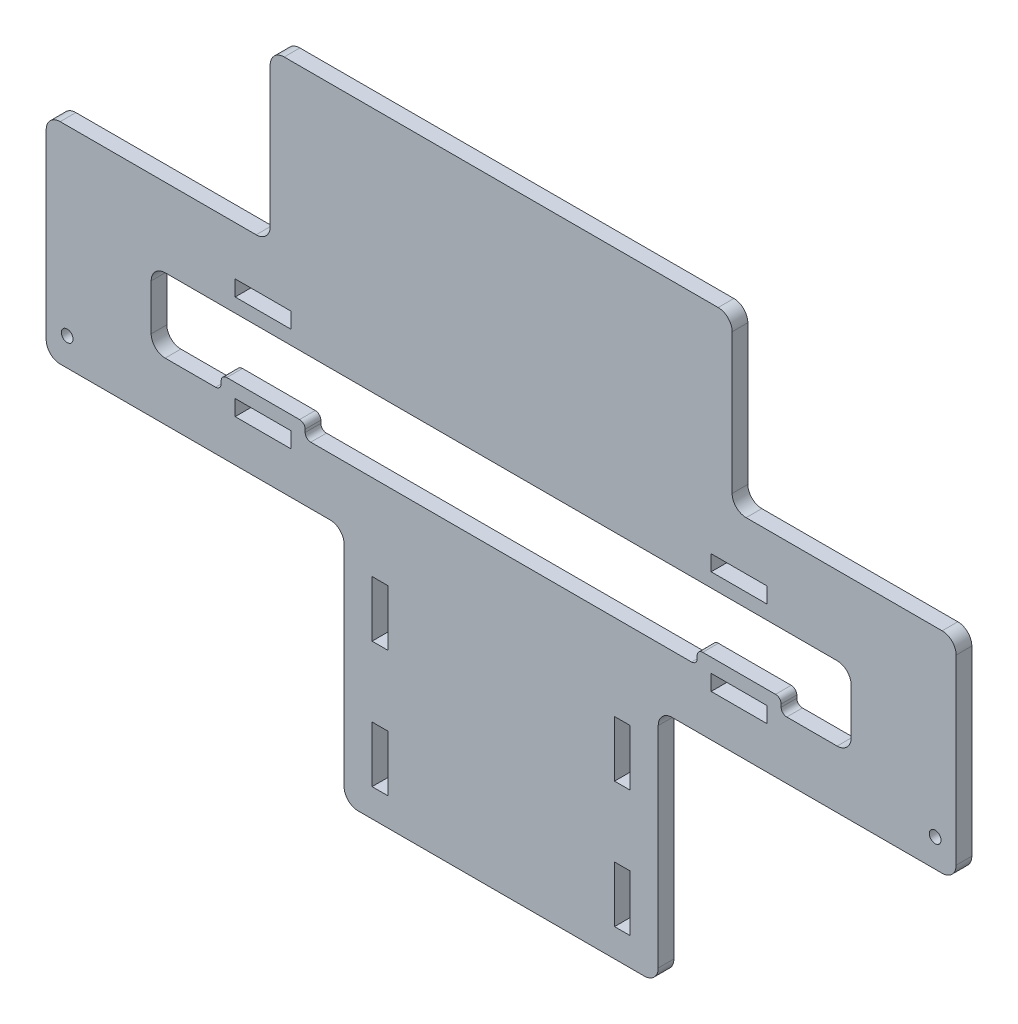
SolidWorks part; units mm, degrees
material "t5ハニカムプラダン"
ref_plane "正面" through (0, 0, 0) normal (0, 0, 1) x (1, 0, 0)
ref_plane "平面" through (0, 0, 0) normal (0, 1, 0) x (1, 0, 0)
ref_plane "右側面" through (0, 0, 0) normal (1, 0, 0) x (0, 0, -1)
sketch "ｽｹｯﾁ1" plane through (0, 0, 0) normal (0, 0, 1) x (1, 0, 0)
  line L0 (0, 0) -> (0, 115) construction
  line L1 (-155, 110) -> (155, 110) construction
  line L2 (-155, 110) -> (-155, -110) construction
  line L3 (-155, -110) -> (155, -110) construction
  line L4 (155, 110) -> (155, -110) construction
  line L5 (-155, 110) -> (155, -110) construction
  line L6 (-155, -110) -> (155, 110) construction
  line L7 (-162.5, 115) -> (162.5, 115)
  line L8 (-162.5, 115) -> (-162.5, -115)
  line L9 (-162.5, -115) -> (162.5, -115)
  line L10 (162.5, 115) -> (162.5, -115)
  line L11 (-162.5, 115) -> (162.5, -115) construction
  line L12 (-162.5, -115) -> (162.5, 115) construction
  line L13 (0, 0) -> (162.5, 0) construction
  circle A0 centre (155, 110) radius 2.1
  circle A1 centre (155, -110) radius 2.1
  circle A2 centre (-155, 110) radius 2.1
  circle A3 centre (-155, -110) radius 2.1
  circle A4 centre (155, -10) radius 2.1
  circle A5 centre (-155, -10) radius 2.1
  point P0 (0, 0)
  point P6 (0, 0)
  dimension "D5" = 4.2
  dimension "D1" = 310
  dimension "D2" = 220
  dimension "D3" = 325
  dimension "D4" = 230
  dimension "D6" = 100
extrude "ﾎﾞｽ - 押し出し1" add sketch "ｽｹｯﾁ1" along normal blind 5.6
sketch "ｽｹｯﾁ2" plane through (0, 0, 5.6) normal (0, 0, 1) x (1, 0, 0)
  line L0 (0, 0) -> (0, 115) construction
  line L1 (162.5, 115) -> (-162.5, 115) construction
  line L2 (40.5, -30) -> (40.5, -50)
  line L3 (-46.1, -30) -> (-40.5, -30)
  line L4 (-46.1, -30) -> (-46.1, -50)
  line L5 (-46.1, -50) -> (-40.5, -50)
  line L6 (-40.5, -30) -> (-40.5, -50)
  line L7 (46.1, -50) -> (40.5, -50)
  line L8 (46.1, -30) -> (46.1, -50)
  line L9 (46.1, -30) -> (40.5, -30)
  line L10 (40.5, -75) -> (40.5, -95)
  line L11 (-46.1, -75) -> (-40.5, -75)
  line L12 (-46.1, -75) -> (-46.1, -95)
  line L13 (-46.1, -95) -> (-40.5, -95)
  line L14 (-40.5, -75) -> (-40.5, -95)
  line L15 (46.1, -95) -> (40.5, -95)
  line L16 (46.1, -75) -> (46.1, -95)
  line L17 (46.1, -75) -> (40.5, -75)
  line L18 (40.5, -30) -> (40.5, -75) construction
  line L19 (-162.5, -115) -> (162.5, -115) construction
  line L20 (75, 0.6) -> (75, -5)
  line L21 (-95, 0.6) -> (-75, 0.6)
  line L22 (-95, 0.6) -> (-95, -5)
  line L23 (-95, -5) -> (-75, -5)
  line L24 (-75, 0.6) -> (-75, -5)
  line L25 (95, -5) -> (75, -5)
  line L26 (95, 0.6) -> (95, -5)
  line L27 (95, 0.6) -> (75, 0.6)
  line L28 (75, 37.6) -> (75, 32)
  line L29 (-95, 37.6) -> (-75, 37.6)
  line L30 (-95, 37.6) -> (-95, 32)
  line L31 (-95, 32) -> (-75, 32)
  line L32 (-75, 37.6) -> (-75, 32)
  line L33 (95, 32) -> (75, 32)
  line L34 (95, 37.6) -> (95, 32)
  line L35 (95, 37.6) -> (75, 37.6)
  dimension "D1" = 5.6
  dimension "D2" = 20
  dimension "D3" = 81
  dimension "D5" = 45
  dimension "D6" = 20
  dimension "D7" = 150
  dimension "D8" = 110
  dimension "D9" = 31.4
  dimension "D4" = 2
extrude "ｶｯﾄ - 押し出し1" cut sketch "ｽｹｯﾁ2" against normal through all
sketch "ｽｹｯﾁ3" plane through (0, 0, 5.6) normal (0, 0, 1) x (1, 0, 0)
  line L0 (0, 0) -> (0, -115) construction
  line L1 (-162.5, -115) -> (162.5, -115) construction
  line L2 (-95, -5) -> (-75, -5) construction
  line L3 (-162.5, -115) -> (-56.1, -115)
  line L4 (-162.5, -115) -> (-162.5, -20)
  line L5 (-162.5, -20) -> (-56.1, -20)
  line L6 (-56.1, -115) -> (-56.1, -20)
  line L7 (-46.1, -75) -> (-46.1, -95) construction
  line L8 (56.1, -115) -> (56.1, -20)
  line L9 (162.5, -20) -> (56.1, -20)
  line L10 (162.5, -115) -> (162.5, -20)
  line L11 (162.5, -115) -> (56.1, -115)
  line L13 (-56.1, -115) -> (56.1, -115)
  line L14 (-56.1, -115) -> (-56.1, -105)
  line L15 (-56.1, -105) -> (56.1, -105)
  line L16 (56.1, -115) -> (56.1, -105)
  line M39 (162.5, -115) -> (162.5, 115)
  line M41 (-162.5, 115) -> (-162.5, -115)
  line M42 (-162.5, -115) -> (162.5, -115)
  circle M43 centre (155, -110) radius 2.1
  circle M44 centre (-155, -110) radius 2.1
  dimension "D1" = 15
  dimension "D2" = 10
  dimension "D3" = 10
extrude "ｶｯﾄ - 押し出し2" cut sketch "ｽｹｯﾁ3" against normal through all contours L6 L5 M42 M41 M44 | L0 L15 L6 M42 | L15 L0 L13 L8 | L9 L8 M39 M42 M43
sketch "ｽｹｯﾁ4" plane through (0, 0, 5.6) normal (0, 0, 1) x (1, 0, 0)
  line L0 (0, 115) -> (0, -105) construction
  line L1 (162.5, 115) -> (-162.5, 115) construction
  line L3 (95, 0.6) -> (75, 0.6) construction
  line L4 (-125, 27) -> (125, 27)
  line L5 (-125, 27) -> (-125, 5.6)
  line L6 (-100, 5.6) -> (-70, 5.6)
  line L7 (125, 27) -> (125, 5.6)
  line L8 (-125, 27) -> (125, 5.6) construction
  line L9 (-125, 5.6) -> (125, 27) construction
  line L10 (75, 32) -> (95, 32) construction
  line L11 (-75, -5) -> (-75, 0.6) construction
  line L12 (-70, 0.6) -> (70, 0.6)
  line L13 (-70, 0.6) -> (-70, 5.6)
  line L14 (0, 5.6) -> (70, 5.6) construction
  line L15 (70, 0.6) -> (70, 5.6)
  line L16 (-70, 0.6) -> (70, 5.6) construction
  line L17 (-70, 5.6) -> (70, 0.6) construction
  line L18 (-75, 0.6) -> (-95, 0.6) construction
  line L19 (-70, 5.6) -> (0, 5.6) construction
  line L20 (70, 5.6) -> (100, 5.6)
  line L21 (-70, 5.6) -> (0, 5.6) construction
  line L22 (0, 5.6) -> (70, 5.6) construction
  line L23 (-95, 0.6) -> (-95, -5) construction
  line L24 (-125, 5.6) -> (-100, 5.6) construction
  line L25 (-125, 5.6) -> (-125, 0.6)
  line L26 (-125, 0.6) -> (-100, 0.6)
  line L27 (-100, 5.6) -> (-100, 0.6)
  line L28 (100, 5.6) -> (100, 0.6)
  line L29 (125, 0.6) -> (100, 0.6)
  line L30 (125, 5.6) -> (125, 0.6)
  line L31 (125, 5.6) -> (100, 5.6) construction
  line L32 (-125, 5.6) -> (-100, 5.6) construction
  line L33 (100, 5.6) -> (125, 5.6) construction
  line L34 (-56.1, -105) -> (56.1, -105) construction
  point P6 (0, 16.3)
  point P15 (85, 32)
  point P16 (0, 3.1)
  dimension "D1" = 5
  dimension "D2" = 5
  dimension "D3" = 250
  dimension "D4" = 5
  dimension "D5" = 5
extrude "ｶｯﾄ - 押し出し3" cut sketch "ｽｹｯﾁ4" against normal through all
sketch "ｽｹｯﾁ5" plane through (0, 0, 5.6) normal (0, 0, 1) x (1, 0, 0)
  line L0 (0, 0.6) -> (0, 115) construction
  line L1 (-162.5, 115) -> (-82.5, 115)
  line L2 (-162.5, 115) -> (-162.5, 55)
  line L3 (-162.5, 55) -> (-82.5, 55)
  line L4 (-82.5, 115) -> (-82.5, 55)
  line L5 (-70, 0.6) -> (70, 0.6) construction
  line L6 (162.5, 115) -> (-162.5, 115) construction
  line L7 (82.5, 115) -> (82.5, 55)
  line L8 (162.5, 55) -> (82.5, 55)
  line L9 (162.5, 115) -> (162.5, 55)
  line L10 (162.5, 115) -> (82.5, 115)
  dimension "D1" = 80
  dimension "D2" = 60
extrude "ｶｯﾄ - 押し出し4" cut sketch "ｽｹｯﾁ5" against normal through all
fillet "ﾌｨﾚｯﾄ1" radius 5 16 edges at (56.1, -20, 2.8) (-56.1, -20, 2.8) (-162.5, -20, 2.8) (162.5, -20, 2.8) (125, 27, 2.8) (125, 0.6, 2.8) (-125, 27, 2.8) (-125, 0.6, 2.8) (56.1, -105, 2.8) (-56.1, -105, 2.8) (82.5, 115, 2.8) (82.5, 55, 2.8) (162.5, 55, 2.8) (-82.5, 55, 2.8) (-82.5, 115, 2.8) (-162.5, 55, 2.8)
fillet "ﾌｨﾚｯﾄ2" radius 2 8 edges at (70, 5.6, 2.8) (70, 0.6, 2.8) (100, 5.6, 2.8) (100, 0.6, 2.8) (-70, 5.6, 2.8) (-70, 0.6, 2.8) (-100, 5.6, 2.8) (-100, 0.6, 2.8)
